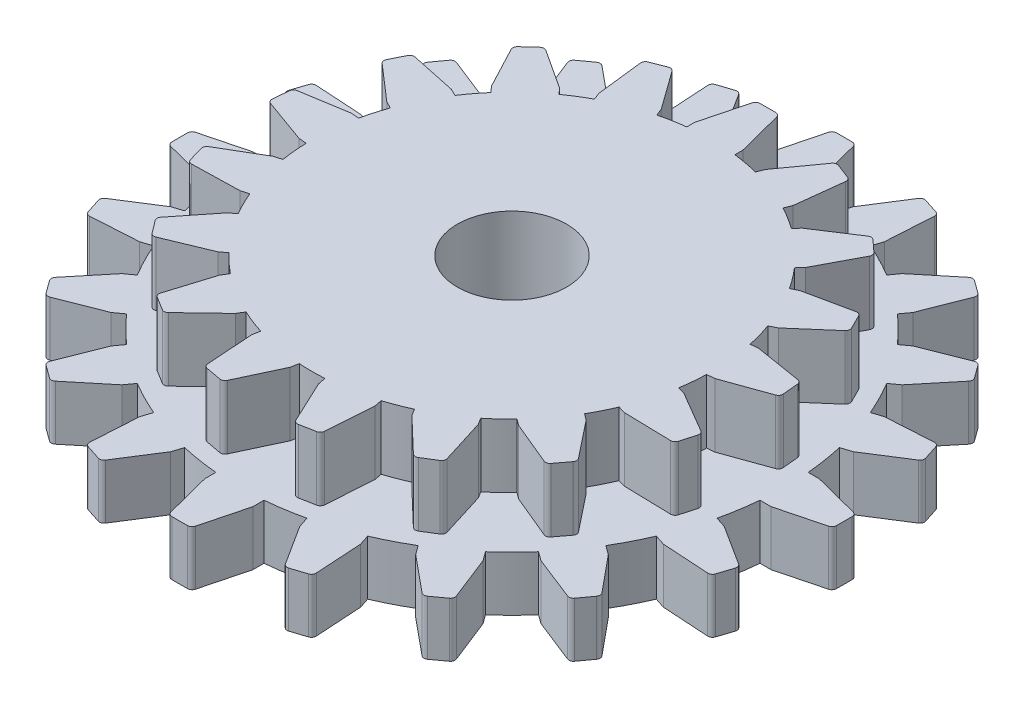
SolidWorks part; units mm, degrees
ref_plane "Front Plane" through (0, 0, 0) normal (0, 0, 1) x (1, 0, 0)
ref_plane "Top Plane" through (0, 0, 0) normal (0, 1, 0) x (1, 0, 0)
ref_plane "Right Plane" through (0, 0, 0) normal (1, 0, 0) x (0, 0, -1)
sketch "Sketch1" plane through (0, 0, 0) normal (0, 0, 1) x (1, 0, 0)
  line L0 (0, 0) -> (0, 6.5)
  line L1 (0, 6.5) -> (11, 6.5)
  line L2 (11, 6.5) -> (11, 3)
  line L3 (11, 3) -> (15, 3)
  line L4 (15, 3) -> (15, 0)
  line L5 (15, 0) -> (0, 0)
  line L6 (3, 6.5) -> (3, 0)
  dimension "D1" = 3.5
  dimension "D2" = 3
  dimension "D3" = 11
  dimension "D4" = 15
  dimension "D5" = 3
revolve "Revolve1" add sketch "Sketch1" angle 360 about L0
sketch "Sketch2" plane through (0, 0, 0) normal (0, 1, 0) x (1, 0, 0)
  line L0 (-1.3233, 14.75) -> (-1.3233, 15.55)
  line L1 (-1.3233, 15.55) -> (-0.625, 18.25)
  line L2 (-0.625, 18.25) -> (0.625, 18.25)
  line L3 (0.625, 18.25) -> (1.3233, 15.55)
  line L4 (1.3233, 15.55) -> (1.3233, 14.75)
  line L5 (1.3233, 14.75) -> (-1.3233, 14.75)
  point P6 (0, 14.75)
  dimension "D1" = 1.25
  dimension "D2" = 14.5
  dimension "D3" = 0.8
  dimension "D4" = 3.5
  dimension "D5" = 14.75
extrude "Boss-Extrude1" add sketch "Sketch2" along normal up to surface (3 mm away) up to face at (0, 3, -15)
fillet "Fillet1" radius 0.25 2 edges at (-0.625, 1.5, -18.25) (0.625, 1.5, -18.25)
pattern_circular "CirPattern1" count 20 over 360 about axis through (0, 0, 0) along (0, 1, 0) of "Fillet1", "Boss-Extrude1"
sketch "Sketch3" plane through (0, 0, 0) normal (0, 1, 0) x (1, 0, 0)
  line L5 (1.3233, 11.35) -> (1.3233, 10.7415)
  line L6 (0.6735, 13.8626) -> (1.3233, 11.35)
  line L7 (-0.4314, 14.05) -> (0.4314, 14.05)
  line L8 (-1.3233, 11.35) -> (-0.6735, 13.8626)
  line L9 (-1.3233, 10.7415) -> (-1.3233, 11.35)
  line L10 (1.3233, 10.7415) -> (-1.3233, 10.7415)
  arc A2 (0.6735, 13.8626) -> (0.4314, 14.05) centre (0.4314, 13.8) ccw
  arc A3 (-0.4314, 14.05) -> (-0.6735, 13.8626) centre (-0.4314, 13.8) ccw
extrude "Boss-Extrude2" add sketch "Sketch3" along normal up to surface (6.5 mm away) up to face at (0, 6.5, -11)
pattern_circular "CirPattern2" count 17 over 360 about axis through (0, 0, 0) along (0, 1, 0) of "Boss-Extrude2"
